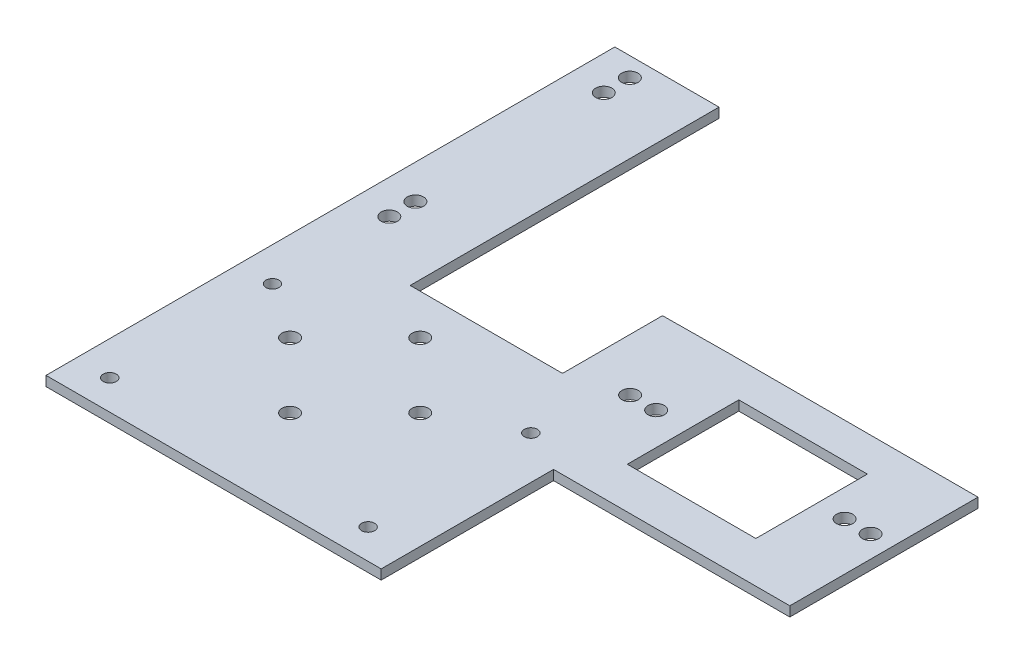
SolidWorks part; units mm, degrees
material "ABS"
ref_plane "Front Plane" through (0, 0, 0) normal (0, 0, 1) x (1, 0, 0)
ref_plane "Top Plane" through (0, 0, 0) normal (0, 1, 0) x (1, 0, 0)
ref_plane "Right Plane" through (0, 0, 0) normal (1, 0, 0) x (0, 0, -1)
sketch "Sketch1" plane through (0, 0, 0) normal (0, 1, 0) x (1, 0, 0)
  line L2 (-100, 76.6422) -> (-100, -98.1576)
  line L3 (-100, -98.1576) -> (3, -98.1576)
  line L5 (-100, 101.8424) -> (99.079, -100.9044) construction
  line L6 (-100, -98.1576) -> (99.9654, 98.1237) construction
  line L10 (75.6041, -45.1959) -> (75.6041, 12.6369)
  line L11 (3, -98.1576) -> (3, -45.1959)
  line L12 (3, -45.1959) -> (75.6041, -45.1959)
  line L13 (75.6041, 12.6369) -> (-0.5896, 12.6369)
  line L15 (-67.9807, 12.6369) -> (-67.9807, 76.6422)
  line L18 (12.9693, 1.7666) -> (52.4736, 1.7666)
  line L19 (12.9693, 1.7666) -> (12.9693, -32.5)
  line L20 (12.9693, -32.5) -> (52.4736, -32.5)
  line L21 (52.4736, 1.7666) -> (52.4736, -32.5)
  line L23 (-67.9807, 12.6369) -> (-67.9807, -18.2712)
  line L24 (-67.9807, -18.2712) -> (-21.1648, -18.2712)
  line L25 (-21.1648, 12.447) -> (-21.1648, -18.2712)
  line L26 (-100, 76.6422) -> (-67.9807, 76.6422)
  line L27 (-0.5896, 12.6369) -> (-21.1648, 12.447)
  circle A0 centre (-52.5, -70.6576) radius 2.5
  circle A2 centre (-72.5, -50.6576) radius 2.5
  circle A3 centre (-52.5, -30.6576) radius 2.5
  circle A4 centre (-32.5, -50.6576) radius 2.5
  circle A5 centre (-5, -13.6576) radius 2.5
  circle A6 centre (60.9, -13.6576) radius 2.5
  circle A7 centre (-89.5, -3.1576) radius 2.5
  circle A8 centre (-89.5, 62.7424) radius 2.5
  circle A33 centre (-89.5, 4.8424) radius 2.5
  circle A34 centre (-89.5, 70.7424) radius 2.5
  circle A35 centre (3, -13.6576) radius 2.5
  circle A36 centre (68.9, -13.6576) radius 2.5
  point P0 (0, 0)
  point P8 (-52.5, -50.6576)
  point P18 (-52.5, -50.6576)
  dimension "D3" = 5
  dimension "D1" = 200
  dimension "D2" = 200
  dimension "D4" = 27.5
  dimension "D5" = 47.5
  dimension "D6" = 20
  dimension "D8" = 65.9
  dimension "D9" = 95
  dimension "D10" = 84.5
  dimension "D11" = 65.9
  dimension "D12" = 95
  dimension "D13" = 37
  dimension "D14" = 2
  dimension "D15" = 2
  dimension "D7" = 4
extrude "Boss-Extrude1" add sketch "Sketch1" along normal blind 3
sketch "Sketch4" plane through (0, 3, 0) normal (0, 1, 0) x (1, 0, 0)
  circle A0 centre (-63.2214, -7.8378) radius 2
  circle A1 centre (-26.5958, -7.8378) radius 2
  circle A2 centre (-89.5634, -89.0071) radius 2
  circle A3 centre (-10.1646, -89.0071) radius 2
  circle A4 centre (-10.1646, -39.0071) radius 2
  circle A5 centre (-89.5634, -39.0071) radius 2
  dimension "D1" = 4
  dimension "D2" = 2
extrude "Cut-Extrude3" cut sketch "Sketch4" against normal blind 10
